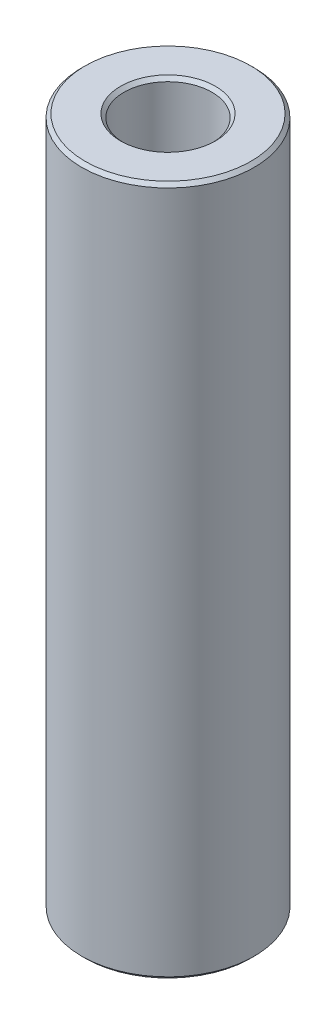
SolidWorks part; units mm, degrees
material "6061-T6 (SS)"
ref_plane "Front Plane" through (0, 0, 0) normal (0, 0, 1) x (1, 0, 0)
ref_plane "Top Plane" through (0, 0, 0) normal (0, 1, 0) x (1, 0, 0)
ref_plane "Right Plane" through (0, 0, 0) normal (1, 0, 0) x (0, 0, -1)
sketch "Sketch1" plane through (0, 0, 0) normal (1, 0, 0) x (0, 0, -1)
  line L0 (0, 2.1339) -> (0, -2.1339) construction
  line L1 (2.55, 19.8) -> (2.75, 20)
  line L2 (2.75, 20) -> (4.8, 20)
  line L3 (2.55, 19.8) -> (2.55, -19.8)
  line L4 (2.75, -20) -> (4.8, -20)
  line L5 (5, 19.8) -> (5, -19.8)
  line L6 (2.55, 20) -> (5, -20) construction
  line L7 (2.55, -20) -> (5, 20) construction
  line L8 (4.8, 20) -> (5, 19.8)
  line L9 (4.8, -20) -> (5, -19.8)
  line L10 (2.55, -19.8) -> (2.75, -20)
  point P0 (3.775, 0)
  point P4 (0, 0)
  dimension "D1" = 2.45
  dimension "D2" = 40
  dimension "D3" = 2.55
revolve "Revolve1" add sketch "Sketch1" angle 360 about L0
